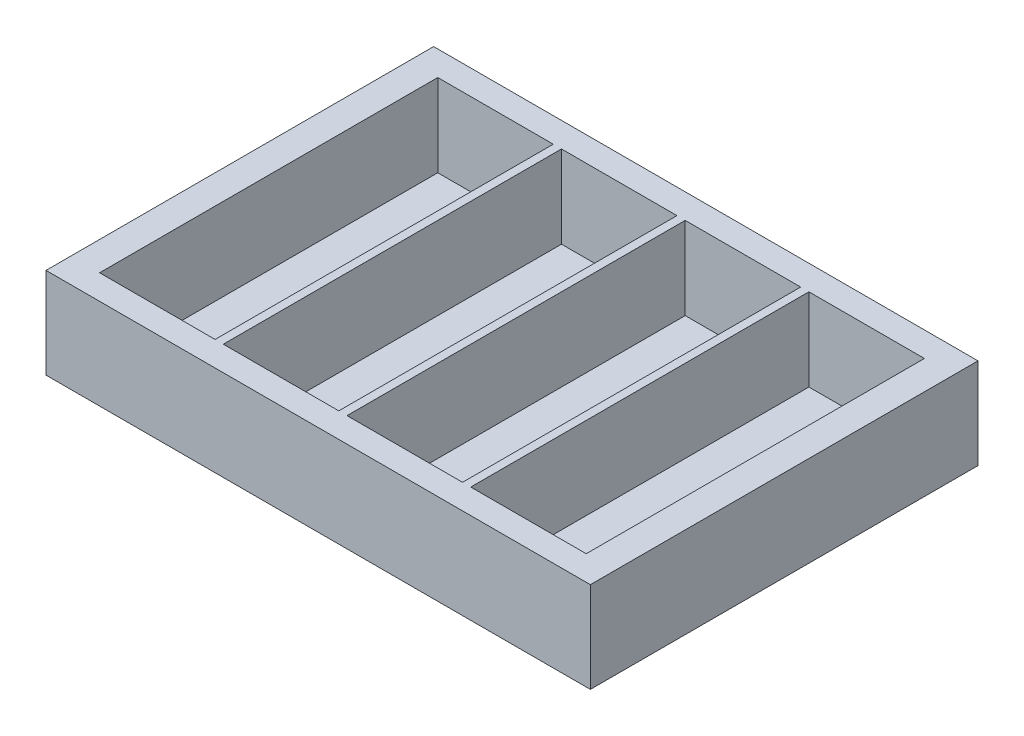
SolidWorks part; units mm, degrees
ref_plane "Front Plane" through (0, 0, 0) normal (0, 0, 1) x (1, 0, 0)
ref_plane "Top Plane" through (0, 0, 0) normal (0, 1, 0) x (1, 0, 0)
ref_plane "Right Plane" through (0, 0, 0) normal (1, 0, 0) x (0, 0, -1)
sketch "Sketch1" plane through (0, 0, 0) normal (0, 1, 0) x (1, 0, 0)
  line L1 (-29.5, 20.5) -> (29.5, 20.5)
  line L2 (-29.5, 20.5) -> (-29.5, -20.5)
  line L3 (-29.5, -20.5) -> (29.5, -20.5)
  line L4 (29.5, 20.5) -> (29.5, -20.5)
  line L5 (-29.5, 20.5) -> (29.5, -20.5) construction
  line L6 (-29.5, -20.5) -> (29.5, 20.5) construction
  line L7 (-33, 23.5) -> (33, 23.5)
  line L8 (-33, 23.5) -> (-33, -23.5)
  line L9 (-33, -23.5) -> (33, -23.5)
  line L10 (33, 23.5) -> (33, -23.5)
  line L11 (-33, 23.5) -> (33, -23.5) construction
  line L12 (-33, -23.5) -> (33, 23.5) construction
  point P0 (0, 0)
  point P6 (0, 0)
  dimension "D1" = 59
  dimension "D2" = 41
  dimension "D3" = 47
  dimension "D4" = 66
extrude "Boss-Extrude1" add sketch "Sketch1" along normal blind 10
sketch "Sketch3" plane through (0, 0, 0) normal (0, -1, 0) x (-1, 0, 0)
  line L1 (33, -23.5) -> (-33, -23.5)
  line L2 (33, -23.5) -> (33, 23.5)
  line L3 (33, 23.5) -> (-33, 23.5)
  line L4 (-33, -23.5) -> (-33, 23.5)
  line L5 (33, -23.5) -> (-33, 23.5) construction
  line L6 (33, 23.5) -> (-33, -23.5) construction
  point P0 (0, 0)
extrude "Boss-Extrude2" add sketch "Sketch3" along normal blind 1
sketch "Sketch6" plane through (0, 10, 0) normal (0, 1, 0) x (1, 0, 0)
  line L1 (0, 27.7024) -> (0, -25.9243)
  line L9 (-15.5, 20.5) -> (-14.5, 20.5)
  line L10 (-15.5, 20.5) -> (-15.5, -20.5)
  line L11 (-15.5, -20.5) -> (-14.5, -20.5)
  line L12 (-14.5, 20.5) -> (-14.5, -20.5)
  line L13 (-15.5, 20.5) -> (-14.5, -20.5) construction
  line L14 (-15.5, -20.5) -> (-14.5, 20.5) construction
  line L19 (-0.5, 20.5) -> (0.5, 20.5)
  line L20 (-0.5, 20.5) -> (-0.5, -20.5)
  line L21 (14.5, 20.5) -> (15.5, 20.5)
  line L22 (14.5, 20.5) -> (14.5, -20.5)
  line L23 (14.5, -20.5) -> (15.5, -20.5)
  line L24 (15.5, 20.5) -> (15.5, -20.5)
  line L25 (14.5, 20.5) -> (15.5, -20.5) construction
  line L26 (14.5, -20.5) -> (15.5, 20.5) construction
  line L27 (-0.5, -20.5) -> (0.5, -20.5)
  line L28 (0.5, 20.5) -> (0.5, -20.5)
  line L29 (-0.5, 20.5) -> (0.5, -20.5) construction
  line L30 (-0.5, -20.5) -> (0.5, 20.5) construction
  point P16 (-15, 0)
  point P17 (0, 0)
  point P19 (15, 0)
  point P20 (-15, 0)
  point P25 (0, 0)
  point P30 (15, 0)
  line M7 (-29.5, 20.5) -> (29.5, 20.5)
  line M9 (29.5, -20.5) -> (-29.5, -20.5)
  dimension "D4" = 1
  dimension "D5" = 1
  dimension "D6" = 41
  dimension "D7" = 1
extrude "Boss-Extrude3" add sketch "Sketch6" against normal blind 10 contours L12 L10 M7 M9 | L20 L1 M7 M9 | L28 L1 M7 M9 | L24 L22 M7 M9
